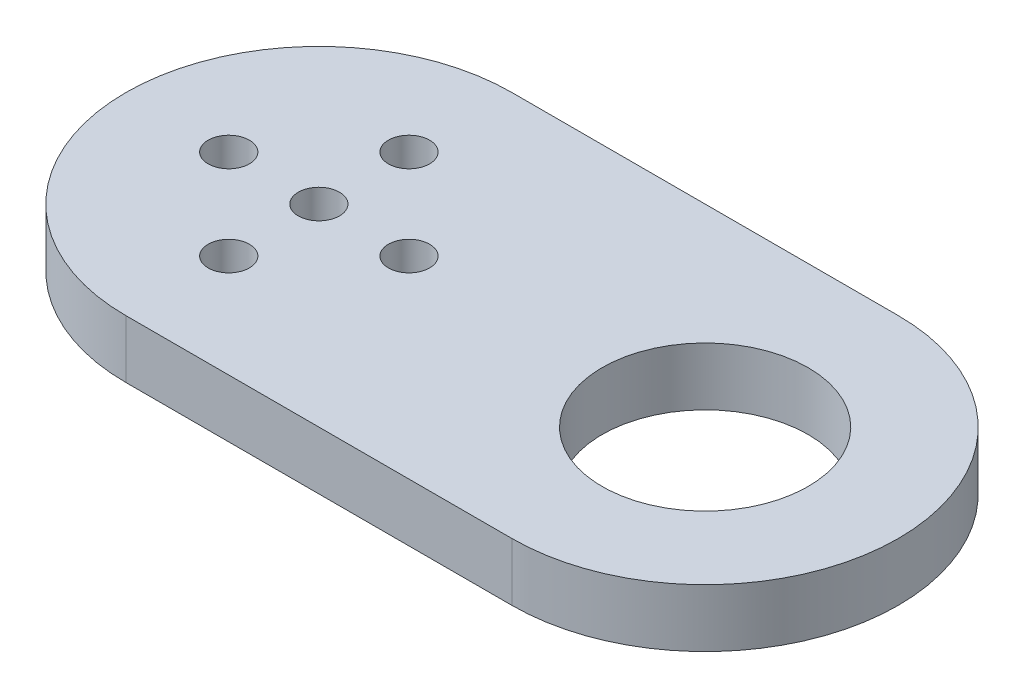
SolidWorks part; units mm, degrees
ref_plane "Front Plane" through (0, 0, 0) normal (0, 0, 1) x (1, 0, 0)
ref_plane "Top Plane" through (0, 0, 0) normal (0, 1, 0) x (1, 0, 0)
ref_plane "Right Plane" through (0, 0, 0) normal (1, 0, 0) x (0, 0, -1)
sketch "Sketch2" plane through (0, 0, 0) normal (0, 1, 0) x (1, 0, 0)
  line L0 (15, 0) -> (-15, 0) construction
  line L1 (15, 15) -> (-15, 15)
  line L2 (15, -15) -> (-15, -15)
  arc A0 (15, 15) -> (15, -15) centre (15, 0) cw
  arc A1 (-15, 15) -> (-15, -15) centre (-15, 0) ccw
  point P4 (0, 0)
  dimension "D1" = 30
  dimension "D2" = 15
  dimension "D3" = 15
extrude "Boss-Extrude1" add sketch "Sketch2" along normal blind 4.5
sketch "Sketch4" plane through (0, 4.5, 0) normal (0, 1, 0) x (1, 0, 0)
  line L0 (-15, 0) -> (-8, 0) construction
  line L1 (15, 0) -> (-15, 0) construction
  line L2 (-15, 0) -> (-8, 0) construction
  circle A0 centre (-15, 0) radius 1.6
  circle A1 centre (-8, 0) radius 1.6
  circle A2 centre (-15, -7) radius 1.6
  circle A3 centre (-22, 0) radius 1.6
  circle A4 centre (-15, 7) radius 1.6
  dimension "D1" = 3.2
  dimension "D2" = 7
  dimension "D3" = 4
extrude "Servo horn holes" cut sketch "Sketch4" against normal through all
sketch "Sketch5" plane through (0, 0, 0) normal (0, -1, 0) x (-1, 0, 0)
  circle A0 centre (-15, 0) radius 8
  dimension "D1" = 16
extrude "Bearing press fit" cut sketch "Sketch5" against normal through all
